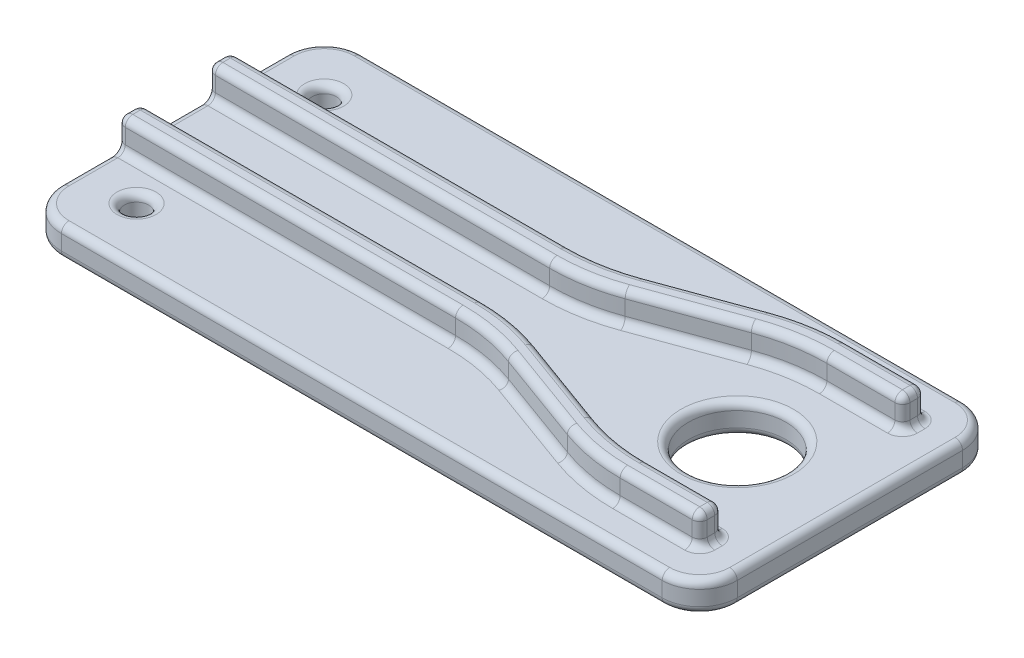
SolidWorks part; units mm, degrees
ref_plane "Front Plane" through (0, 0, 0) normal (0, 0, 1) x (1, 0, 0)
ref_plane "Top Plane" through (0, 0, 0) normal (0, 1, 0) x (1, 0, 0)
ref_plane "Right Plane" through (0, 0, 0) normal (1, 0, 0) x (0, 0, -1)
sketch "Sketch1" plane through (0, 0, 0) normal (0, 1, 0) x (1, 0, 0)
  line L9 (0, 0) -> (90, 0)
  line L10 (0, 0) -> (0, 40)
  line L11 (0, 40) -> (90, 40)
  line L12 (90, 0) -> (90, 40)
  circle A0 centre (75, 20) radius 6.5
  circle A1 centre (7.5, 32.5) radius 1.6
  circle A2 centre (7.5, 7.5) radius 1.6
  point P12 (0, 0)
  point P13 (0, 0)
  point P14 (90, 20)
  dimension "D3" = 3.2
  dimension "D4" = 13
  dimension "D1" = 40
  dimension "D2" = 90
  dimension "D5" = 7.5
  dimension "D6" = 7.5
  dimension "D7" = 7.5
  dimension "D8" = 15
extrude "Boss-Extrude1" add sketch "Sketch1" along normal blind 4
fillet "Fillet1" radius 5 2 edges at (0, 2, -40) (0, 2, 0)
fillet "Fillet2" radius 5 2 edges at (90, 2, 0) (90, 2, -40)
sketch "Sketch2" plane through (0, 4, 0) normal (0, 1, 0) x (1, 0, 0)
  line L0 (0, 27.5) -> (0, 24.5)
  line L17 (0, 24.5) -> (49.9229, 24.5)
  line L18 (49.9229, 24.5) -> (70.529, 32)
  line L19 (70.529, 32) -> (85, 32)
  line L20 (85, 32) -> (85, 35)
  line L21 (85, 35) -> (70, 35)
  line L22 (70, 35) -> (49.3939, 27.5)
  line L23 (49.3939, 27.5) -> (0, 27.5)
  line L24 (85, 40) -> (5, 40) construction
  line L25 (90, 5) -> (90, 35) construction
  line L26 (0, 35) -> (0, 5) construction
  line L27 (0, 15.5) -> (49.9229, 15.5)
  line L28 (49.9229, 15.5) -> (70.529, 8)
  line L29 (70.529, 8) -> (85, 8)
  line L30 (85, 8) -> (85, 5)
  line L31 (85, 5) -> (70, 5)
  line L32 (70, 5) -> (49.3939, 12.5)
  line L33 (49.3939, 12.5) -> (0, 12.5)
  line L34 (0, 12.5) -> (0, 15.5)
  line L35 (5, 0) -> (85, 0) construction
  point P24 (0, 0)
  dimension "D1" = 3
  dimension "D2" = 3
  dimension "D3" = 200
  dimension "D4" = 12.5
  dimension "D5" = 5
  dimension "D6" = 5
  dimension "D7" = 0
  dimension "D8" = 15
  dimension "D9" = 12.5
  dimension "D10" = 200
  dimension "D11" = 5
  dimension "D12" = 3
extrude "Boss-Extrude2" add sketch "Sketch2" along normal blind 4
fillet "Fillet3" radius 25 8 edges at (70.529, 6, -8) (70, 6, -35) (49.3939, 6, -27.5) (49.9229, 6, -15.5) (70.529, 6, -32) (49.9229, 6, -24.5) (70, 6, -5) (49.3939, 6, -12.5)
fillet "Fillet4" radius 1 4 edges at (85, 6, -8) (85, 6, -5) (85, 6, -35) (85, 6, -32)
fillet "Fillet5" radius 1 26 edges at (22.4929, 4, -27.5) (49.3269, 4, -27.8798) (59.697, 4, -31.25) (70.067, 4, -34.6202) (79.2041, 4, -35) (84.7071, 4, -34.7071) (85, 4, -33.5) (84.7071, 4, -32.2929) (79.4686, 4, -32) (70.596, 4, -31.6202) (60.2259, 4, -28.25) (49.8559, 4, -24.8798) (22.7574, 4, -15.5) (49.8559, 4, -15.1202) (60.2259, 4, -11.75) (70.596, 4, -8.3798) (79.4686, 4, -8) (84.7071, 4, -7.7071) (85, 4, -6.5) (84.7071, 4, -5.2929) (79.2041, 4, -5) (70.067, 4, -5.3798) (59.697, 4, -8.75) (49.3269, 4, -12.1202) (22.7574, 4, -24.5) (22.4929, 4, -12.5)
fillet "Fillet6" radius 1 26 edges at (22.7574, 8, -15.5) (49.8559, 8, -15.1202) (60.2259, 8, -11.75) (70.596, 8, -8.3798) (79.4686, 8, -8) (84.7071, 8, -7.7071) (85, 8, -6.5) (84.7071, 8, -5.2929) (79.2041, 8, -5) (70.067, 8, -5.3798) (59.697, 8, -8.75) (49.3269, 8, -12.1202) (22.4929, 8, -27.5) (49.3269, 8, -27.8798) (59.697, 8, -31.25) (70.067, 8, -34.6202) (79.2041, 8, -35) (84.7071, 8, -34.7071) (85, 8, -33.5) (84.7071, 8, -32.2929) (79.4686, 8, -32) (70.596, 8, -31.6202) (60.2259, 8, -28.25) (49.8559, 8, -24.8798) (22.4929, 8, -12.5) (22.7574, 8, -24.5)
fillet "Fillet7" radius 1 8 edges at (1.4645, 0, -1.4645) (0, 0, -20) (1.4645, 0, -38.5355) (45, 0, -40) (88.5355, 0, -38.5355) (90, 0, -20) (88.5355, 0, -1.4645) (45, 0, 0)
fillet "Fillet8" radius 1 24 edges at (1.4645, 4, -1.4645) (0, 4, -8.25) (0, 4.2929, -12.2071) (0, 6, -12.5) (0, 7.7071, -12.7929) (0, 8, -14) (0, 7.7071, -15.2071) (0, 6, -15.5) (0, 4.2929, -15.7929) (0, 4, -20) (0, 4.2929, -24.2071) (0, 6, -24.5) (0, 7.7071, -24.7929) (0, 8, -26) (0, 7.7071, -27.2071) (0, 6, -27.5) (0, 4.2929, -27.7929) (0, 4, -31.75) (1.4645, 4, -38.5355) (45, 4, -40) (88.5355, 4, -38.5355) (90, 4, -20) (88.5355, 4, -1.4645) (45, 4, 0)
fillet "Fillet9" radius 1 6 edges at (7.5, 4, -5.9) (7.5, 4, -30.9) (75, 4, -13.5) (75, 0, -13.5) (7.5, 0, -5.9) (7.5, 0, -30.9)
